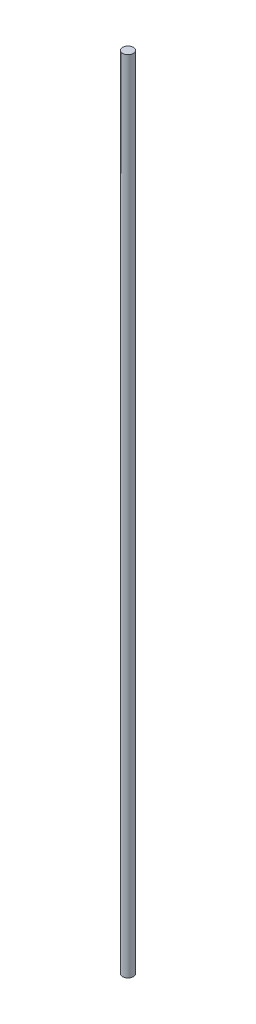
SolidWorks part; units mm, degrees
ref_plane "前视基准面" through (0, 0, 0) normal (0, 0, 1) x (1, 0, 0)
ref_plane "上视基准面" through (0, 0, 0) normal (0, 1, 0) x (1, 0, 0)
ref_plane "右视基准面" through (0, 0, 0) normal (1, 0, 0) x (0, 0, -1)
sketch "草图1" plane through (0, 0, 0) normal (0, 1, 0) x (1, 0, 0)
  circle A0 centre (0, 0) radius 3
  dimension "D1" = 6
extrude "凸台-拉伸1" add sketch "草图1" along normal blind 450
